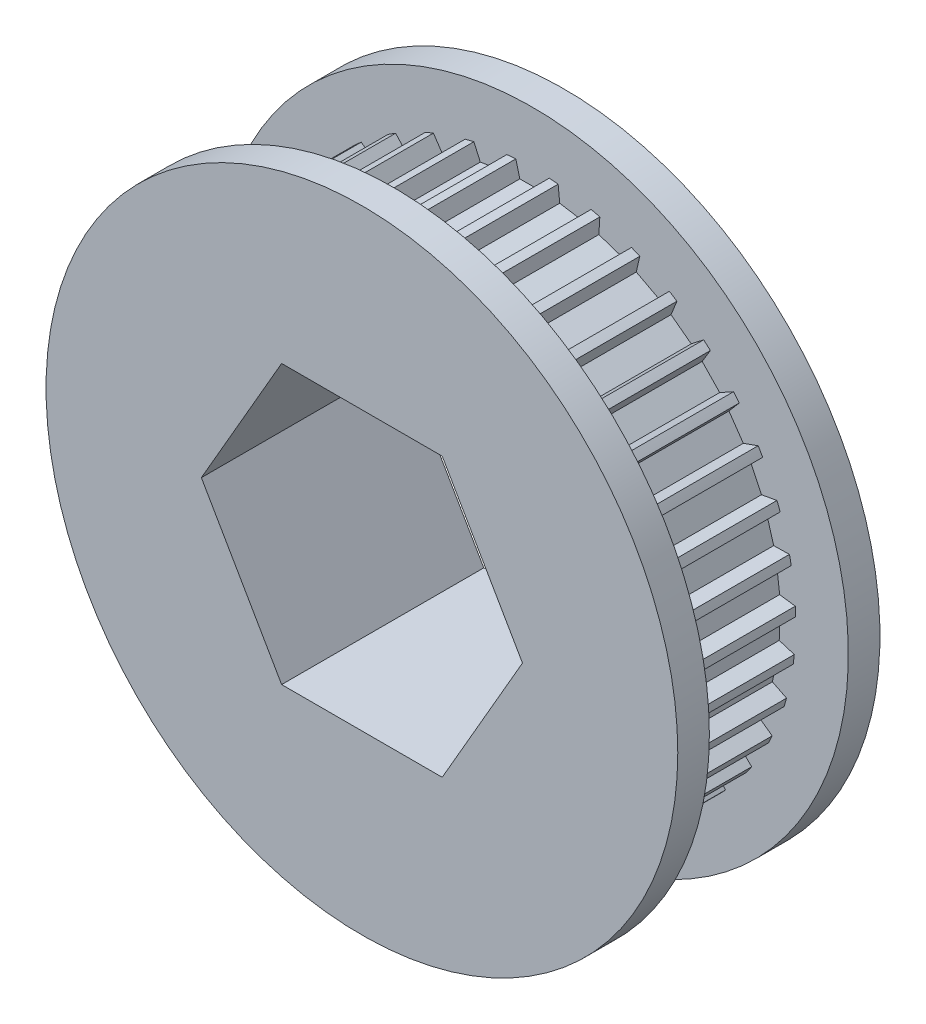
SolidWorks part; units mm, degrees
ref_plane "Front Plane" through (0, 0, 0) normal (0, 0, 1) x (1, 0, 0)
ref_plane "Top Plane" through (0, 0, 0) normal (0, 1, 0) x (1, 0, 0)
ref_plane "Right Plane" through (0, 0, 0) normal (1, 0, 0) x (0, 0, -1)
sketch "Sketch1" plane through (0, 0, 0) normal (0, 0, 1) x (1, 0, 0)
  circle A0 centre (0, 0) radius 12.5
  dimension "D1" = 25
extrude "Boss-Extrude1" add sketch "Sketch1" along normal mid plane 6.6
sketch "Sketch3" plane through (0, 0, 3.3) normal (0, 0, 1) x (1, 0, 0)
  circle A0 centre (0, 0) radius 15
  dimension "D1" = 30
sketch "Sketch2" plane through (0, 0, -3.3) normal (0, 0, -1) x (-1, 0, 0)
  circle A0 centre (0, 0) radius 15
  dimension "D1" = 30
sketch "Sketch4" plane through (0, 0, 3.3) normal (0, 0, 1) x (1, 0, 0)
  line L0 (-0.6, 11.75) -> (0.6, 11.75)
  line L1 (0.6, 11.75) -> (0.8, 12.5)
  line L2 (0.8, 12.5) -> (-0.8, 12.5)
  line L3 (-0.8, 12.5) -> (-0.6, 11.75)
  circle A0 centre (0, 0) radius 12.5 construction
  point P10 (0, 11.75)
  dimension "D1" = 1.2
  dimension "D2" = 1.6
  dimension "D3" = 0.75
extrude "Cut-Extrude1" cut sketch "Sketch4" against normal up to surface (6.6 mm away) and the other way through all up to face at (12.5, 0, -3.3)
pattern_circular "CirPattern2" count 39 over 360 about axis through (0, 0, 0) along (0, 0, 1) of "Cut-Extrude1"
extrude "Boss-Extrude3" add sketch "Sketch2" along normal blind 1.5
extrude "Boss-Extrude4" add sketch "Sketch3" along normal blind 1.5 contours A0
sketch "Sketch5" plane through (0, 0, 4.8) normal (0, 0, 1) x (1, 0, 0)
  line L1 (7.625, 0) -> (3.8125, 6.6034)
  line L2 (3.8125, 6.6034) -> (-3.8125, 6.6034)
  line L3 (-3.8125, 6.6034) -> (-7.625, 0)
  line L4 (-7.625, 0) -> (-3.8125, -6.6034)
  line L5 (-3.8125, -6.6034) -> (3.8125, -6.6034)
  line L6 (3.8125, -6.6034) -> (7.625, 0)
  circle A0 centre (0, 0) radius 6.6034 construction
  dimension "D1" = 15.25
extrude "Cut-Extrude2" cut sketch "Sketch5" against normal through all both and the other way through all
